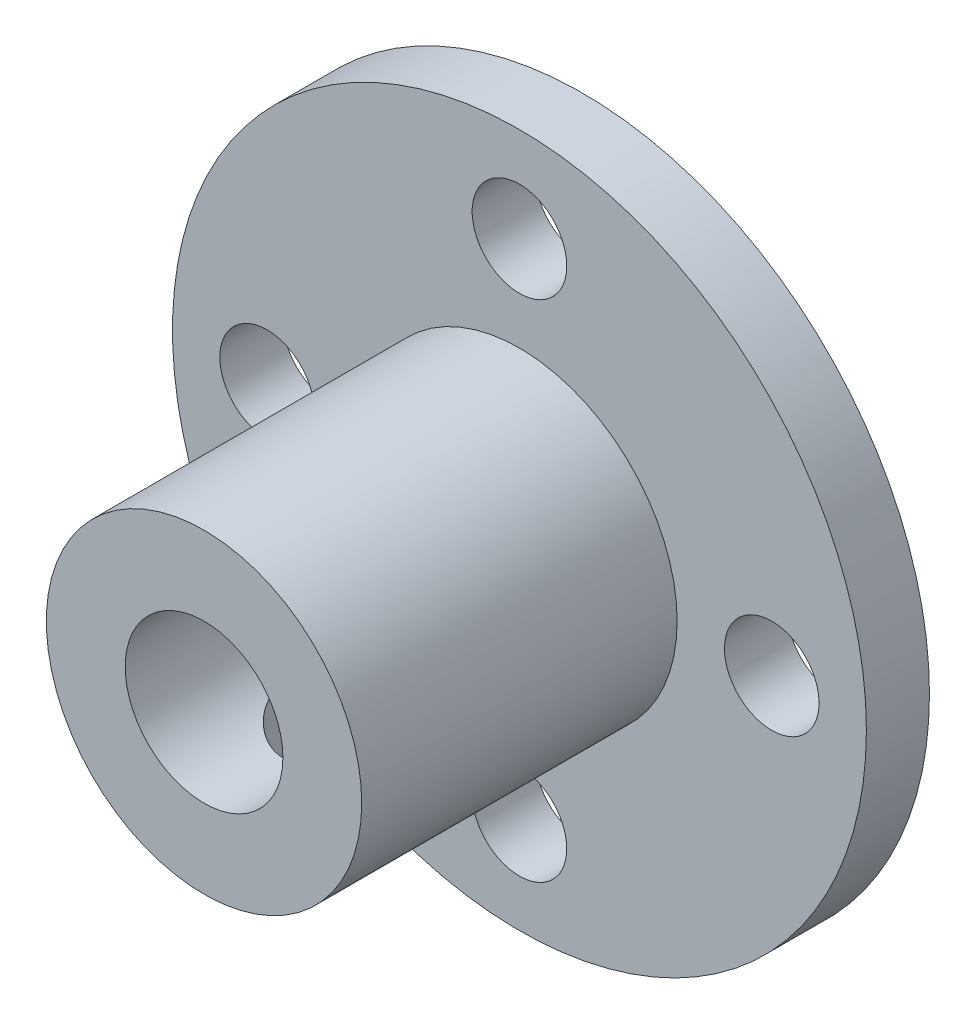
SolidWorks part; units mm, degrees
ref_plane "Front Plane" through (0, 0, 0) normal (0, 0, 1) x (1, 0, 0)
ref_plane "Top Plane" through (0, 0, 0) normal (0, 1, 0) x (1, 0, 0)
ref_plane "Right Plane" through (0, 0, 0) normal (1, 0, 0) x (0, 0, -1)
sketch "Sketch2" plane through (0, 0, 0) normal (0, 0, 1) x (1, 0, 0)
  circle A0 centre (0, 0) radius 11
  dimension "D1" = 22
extrude "Boss-Extrude1" add sketch "Sketch2" along normal blind 2
sketch "Sketch3" plane through (0, 0, 2) normal (0, 0, 1) x (1, 0, 0)
  circle A0 centre (0, 0) radius 5
  dimension "D1" = 10
extrude "Boss-Extrude2" add sketch "Sketch3" along normal blind 10
sketch "Sketch4" plane through (0, 0, 12) normal (0, 0, 1) x (1, 0, 0)
  circle A0 centre (0, 0) radius 2.5
  dimension "D1" = 5
extrude "Cut-Extrude1" cut sketch "Sketch4" against normal through all
sketch "Sketch5" plane through (0, 0, 0) normal (0, 1, 0) x (1, 0, 0)
  line L0 (11, 0) -> (-11, 0) construction
  line L2 (5, -12) -> (5, -2) construction
  circle A0 centre (0, -8) radius 1.5
  point P0 (0, -8)
  dimension "D3" = 3
  dimension "D1" = 8
  dimension "D2" = 5
extrude "Cut-Extrude2" cut sketch "Sketch5" against normal blind 10
sketch "Sketch6" plane through (0, 0, 2) normal (0, 0, 1) x (1, 0, 0)
  circle A0 centre (0, 8) radius 1.5
  dimension "D1" = 3
  dimension "D2" = 8
  dimension "D3" = 0
extrude "Cut-Extrude3" cut sketch "Sketch6" against normal through all
pattern_circular "CirPattern1" count 4 over 360 about axis through (0, 0, 0) along (0, 0, 1) of "Cut-Extrude3"
